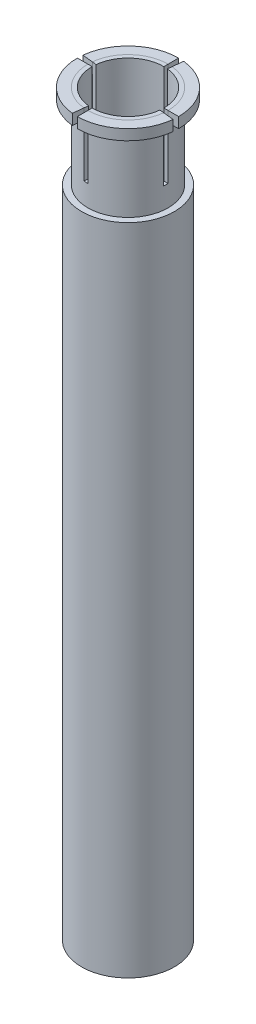
SolidWorks part; units mm, degrees
ref_plane "前视基准面" through (0, 0, 0) normal (0, 0, 1) x (1, 0, 0)
ref_plane "上视基准面" through (0, 0, 0) normal (0, 1, 0) x (1, 0, 0)
ref_plane "右视基准面" through (0, 0, 0) normal (1, 0, 0) x (0, 0, -1)
sketch "草图1" plane through (0, 0, 0) normal (0, 1, 0) x (1, 0, 0)
  circle A0 centre (0, 0) radius 17
  dimension "D1" = 34
extrude "拉伸-薄壁1" add sketch "草图1" along normal blind 50 thin
cosmetic thread "装饰螺纹线2" parameters "D1"=40, "D2"=36
sketch "草图3" plane through (0, 50, 0) normal (0, 1, 0) x (1, 0, 0)
  line L0 (0, 0) -> (0, 19)
  line L1 (0, 19) -> (2, 19)
  line L2 (2, 19) -> (0, 0)
  circle A0 centre (0, 0) radius 19 construction
  dimension "D1" = 2
extrude "切除-拉伸1" cut sketch "草图3" against normal blind 30
pattern_circular "阵列(圆周)1" count 4 over 360 about axis through (0, 50, 0) along (0, -1, 0) of "切除-拉伸1"
sketch "草图4" plane through (0, 50, 0) normal (0, 1, 0) x (1, 0, 0)
  line L0 (0, 19) -> (0, 24)
  line L1 (1.989, 18.8956) -> (2.5124, 23.8681)
  line L2 (19, 0) -> (24, 0)
  line L3 (18.8956, -1.989) -> (23.8681, -2.5124)
  line L4 (0, -19) -> (0, -24)
  line L5 (-1.989, -18.8956) -> (-2.5124, -23.8681)
  line L6 (-19, 0) -> (-24, 0)
  line L7 (-18.8956, 1.989) -> (-23.8681, 2.5124)
  arc A0 (0, 19) -> (-18.8956, 1.989) centre (0, 0) ccw
  arc A1 (0, 24) -> (-23.8681, 2.5124) centre (0, 0) ccw
  arc A2 (-19, 0) -> (-1.989, -18.8956) centre (0, 0) ccw
  arc A3 (-24, 0) -> (-2.5124, -23.8681) centre (0, 0) ccw
  arc A4 (19, 0) -> (1.989, 18.8956) centre (0, 0) ccw
  arc A5 (24, 0) -> (2.5124, 23.8681) centre (0, 0) ccw
  arc A6 (0, -19) -> (18.8956, -1.989) centre (0, 0) ccw
  arc A7 (0, -24) -> (23.8681, -2.5124) centre (0, 0) ccw
  point P26 (0, 0)
  dimension "D1" = 48
  dimension "D2" = 4
extrude "凸台-拉伸1" add sketch "草图4" against normal blind 5 separate body
ref_plane "基准面1" through (0, 10, 0) normal (0, 1, 0) x (1, 0, 0)
sketch "草图6" plane through (0, 10, 0) normal (0, 1, 0) x (1, 0, 0)
  circle A0 centre (0, 0) radius 20
  circle A1 centre (0, 0) radius 22
  dimension "D1" = 40
  dimension "D2" = 44
extrude "凸台-拉伸3" add sketch "草图6" against normal blind 310
sketch "草图7" plane through (0, 10, 0) normal (0, 1, 0) x (1, 0, 0)
  circle A1 centre (0, 0) radius 20
  circle A2 centre (0, 0) radius 19
  dimension "D1" = 40
  dimension "D2" = 38
extrude "凸台-拉伸4" add sketch "草图7" against normal up to surface (10 mm away) up to face at (19, 0, 0)
